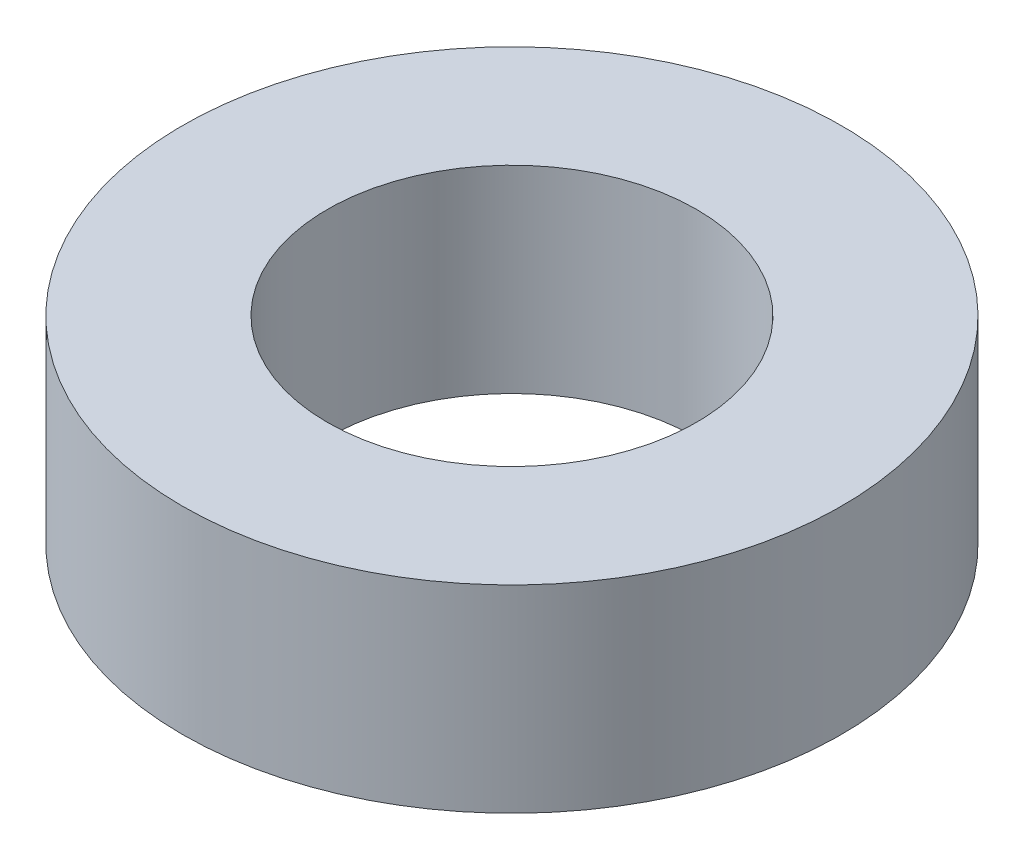
SolidWorks part; units mm, degrees
material "6061 Alloy"
ref_plane "Front Plane" through (0, 0, 0) normal (0, 0, 1) x (1, 0, 0)
ref_plane "Top Plane" through (0, 0, 0) normal (0, 1, 0) x (1, 0, 0)
ref_plane "Right Plane" through (0, 0, 0) normal (1, 0, 0) x (0, 0, -1)
sketch "Sketch1" plane through (0, 0, 0) normal (0, 1, 0) x (1, 0, 0)
  circle A0 centre (0, 0) radius 12.5
  circle A1 centre (0, 0) radius 7
  dimension "D1" = 25
  dimension "D2" = 14
extrude "Boss-Extrude1" add sketch "Sketch1" along normal blind 7.5
